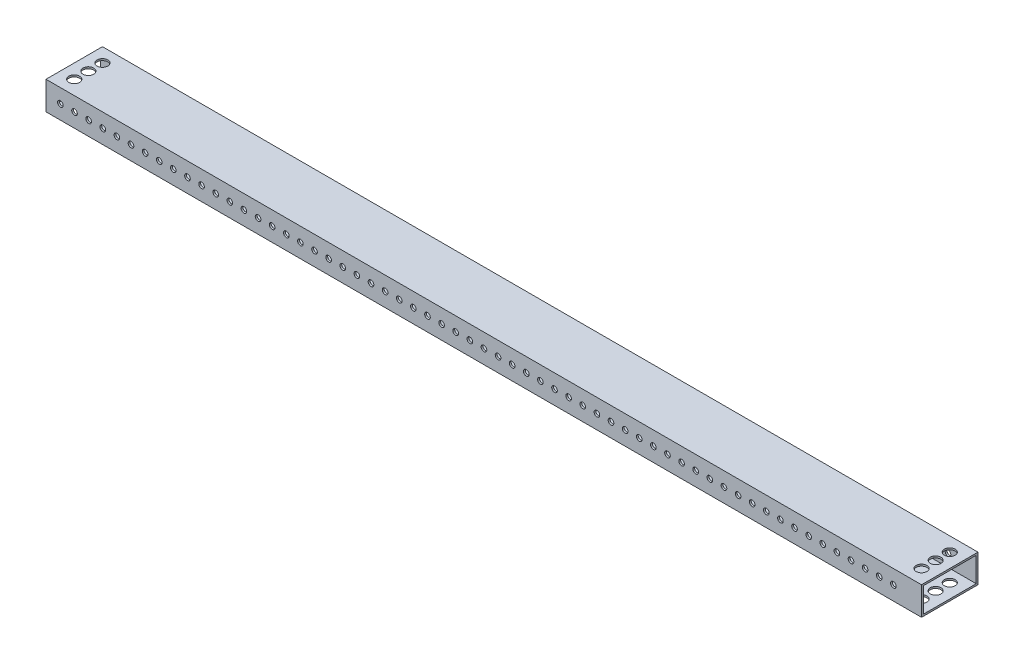
SolidWorks part; units mm, degrees
ref_plane "Front Plane" through (0, 0, 0) normal (0, 0, 1) x (1, 0, 0)
ref_plane "Top Plane" through (0, 0, 0) normal (0, 1, 0) x (1, 0, 0)
ref_plane "Right Plane" through (0, 0, 0) normal (1, 0, 0) x (0, 0, -1)
sketch "Sketch1" plane through (0, 0, 0) normal (0, 1, 0) x (1, 0, 0)
  line L1 (393.7901, 25.4) -> (-393.7901, 25.4)
  line L2 (393.7901, 25.4) -> (393.7901, -25.4)
  line L3 (393.7901, -25.4) -> (-393.7901, -25.4)
  line L4 (-393.7901, 25.4) -> (-393.7901, -25.4)
  line L5 (393.7901, 25.4) -> (-393.7901, -25.4) construction
  line L6 (393.7901, -25.4) -> (-393.7901, 25.4) construction
  point P0 (0, 0)
  dimension "D1" = 50.8
extrude "Boss-Extrude1" add sketch "Sketch1" along normal blind 25.4
sketch "Sketch2" plane through (-393.7901, 0, 0) normal (-1, 0, 0) x (0, 0, 1)
  line L1 (23.7937, 23.7836) -> (-23.7836, 23.7836)
  line L2 (23.7937, 23.7836) -> (23.7937, 1.6265)
  line L3 (23.7937, 1.6265) -> (-23.7836, 1.6265)
  line L4 (-23.7836, 23.7836) -> (-23.7836, 1.6265)
  line L6 (-25.4, 25.4) -> (-25.4, 0) construction
  line L7 (25.4, 25.4) -> (25.4, 0) construction
  point P8 (0, 0)
  point P9 (0, 0)
  dimension "D1" = 2.286
  dimension "D2" = 2.286
  dimension "D3" = 1.6164
  dimension "D4" = 1.6063
extrude "Cut-Extrude1" cut sketch "Sketch2" against normal through all
sketch "Sketch3" plane through (0, 0, 25.4) normal (0, 0, 1) x (1, 0, 0)
  line L0 (-1393.7901, 12.7) -> (48606.2099, 12.7) construction
  line L1 (-393.7901, 25.4) -> (-393.7901, 0) construction
  circle A1 centre (-380.8361, 12.7) radius 2.54
  circle A2 centre (-368.1361, 12.7) radius 2.54
  circle A3 centre (-355.4361, 12.7) radius 2.54
  circle A4 centre (-342.7361, 12.7) radius 2.54
  circle A5 centre (-330.0361, 12.7) radius 2.54
  circle A6 centre (-317.3361, 12.7) radius 2.54
  circle A7 centre (-304.6361, 12.7) radius 2.54
  circle A8 centre (-291.9361, 12.7) radius 2.54
  circle A9 centre (-279.2361, 12.7) radius 2.54
  circle A10 centre (-266.5361, 12.7) radius 2.54
  circle A11 centre (-253.8361, 12.7) radius 2.54
  circle A12 centre (-241.1361, 12.7) radius 2.54
  circle A13 centre (-228.4361, 12.7) radius 2.54
  circle A14 centre (-215.7361, 12.7) radius 2.54
  circle A15 centre (-203.0361, 12.7) radius 2.54
  circle A16 centre (-190.3361, 12.7) radius 2.54
  circle A17 centre (-177.6361, 12.7) radius 2.54
  circle A18 centre (-164.9361, 12.7) radius 2.54
  circle A19 centre (-152.2361, 12.7) radius 2.54
  circle A20 centre (-139.5361, 12.7) radius 2.54
  circle A21 centre (-126.8361, 12.7) radius 2.54
  circle A22 centre (-114.1361, 12.7) radius 2.54
  circle A23 centre (-101.4361, 12.7) radius 2.54
  circle A24 centre (-88.7361, 12.7) radius 2.54
  circle A25 centre (-76.0361, 12.7) radius 2.54
  circle A26 centre (-63.3361, 12.7) radius 2.54
  circle A27 centre (-50.6361, 12.7) radius 2.54
  circle A28 centre (-37.9361, 12.7) radius 2.54
  circle A29 centre (-25.2361, 12.7) radius 2.54
  circle A30 centre (-12.5361, 12.7) radius 2.54
  circle A31 centre (0.1639, 12.7) radius 2.54
  circle A32 centre (12.8639, 12.7) radius 2.54
  circle A33 centre (25.5639, 12.7) radius 2.54
  circle A34 centre (38.2639, 12.7) radius 2.54
  circle A35 centre (50.9639, 12.7) radius 2.54
  circle A36 centre (63.6639, 12.7) radius 2.54
  circle A37 centre (76.3639, 12.7) radius 2.54
  circle A38 centre (89.0639, 12.7) radius 2.54
  circle A39 centre (101.7639, 12.7) radius 2.54
  circle A40 centre (114.4639, 12.7) radius 2.54
  circle A41 centre (127.1639, 12.7) radius 2.54
  circle A42 centre (139.8639, 12.7) radius 2.54
  circle A43 centre (152.5639, 12.7) radius 2.54
  circle A44 centre (165.2639, 12.7) radius 2.54
  circle A45 centre (177.9639, 12.7) radius 2.54
  circle A46 centre (190.6639, 12.7) radius 2.54
  circle A47 centre (203.3639, 12.7) radius 2.54
  circle A48 centre (216.0639, 12.7) radius 2.54
  circle A49 centre (228.7639, 12.7) radius 2.54
  circle A50 centre (241.4639, 12.7) radius 2.54
  circle A51 centre (254.1639, 12.7) radius 2.54
  circle A52 centre (266.8639, 12.7) radius 2.54
  circle A53 centre (279.5639, 12.7) radius 2.54
  circle A54 centre (292.2639, 12.7) radius 2.54
  circle A55 centre (304.9639, 12.7) radius 2.54
  circle A56 centre (317.6639, 12.7) radius 2.54
  circle A57 centre (330.3639, 12.7) radius 2.54
  circle A58 centre (343.0639, 12.7) radius 2.54
  circle A59 centre (355.7639, 12.7) radius 2.54
  circle A60 centre (368.4639, 12.7) radius 2.54
  point P5 (-393.7901, 12.7)
  dimension "D1" = 5.08
  dimension "D2" = 12.954
  dimension "D4" = 12.7
  dimension "D3" = 60
extrude "Cut-Extrude2" cut sketch "Sketch3" against normal through all
sketch "Sketch4" plane through (0, 25.4, 0) normal (0, 1, 0) x (1, 0, 0)
  line L0 (-1393.7901, 0) -> (48606.2099, 0) construction
  line L1 (-393.7901, 25.4) -> (-393.7901, -25.4) construction
  line L2 (-1388.247, 12.7) -> (48611.753, 12.7) construction
  line L3 (-1379.4121, -12.7) -> (48620.5879, -12.7) construction
  line L4 (-393.7901, -25.4) -> (393.7901, -25.4) construction
  line L5 (0, 25.4) -> (0, -25.4) construction
  line L6 (393.7901, 25.4) -> (-393.7901, 25.4) construction
  circle A0 centre (-381.0901, 12.7) radius 4.826
  circle A2 centre (-381.0901, -12.7) radius 4.826
  circle A3 centre (-381.0901, 0) radius 4.826
  circle A4 centre (381.0901, 12.7) radius 4.826
  circle A5 centre (381.0901, 0) radius 4.826
  circle A6 centre (381.0901, -12.7) radius 4.826
  point P5 (-393.7901, 0)
  dimension "D1" = 9.652
  dimension "D5" = 12.7
  dimension "D6" = 9.652
  dimension "D2" = 12.7
  dimension "D3" = 12.7
  dimension "D4" = 12.7
extrude "Cut-Extrude3" cut sketch "Sketch4" against normal through all
